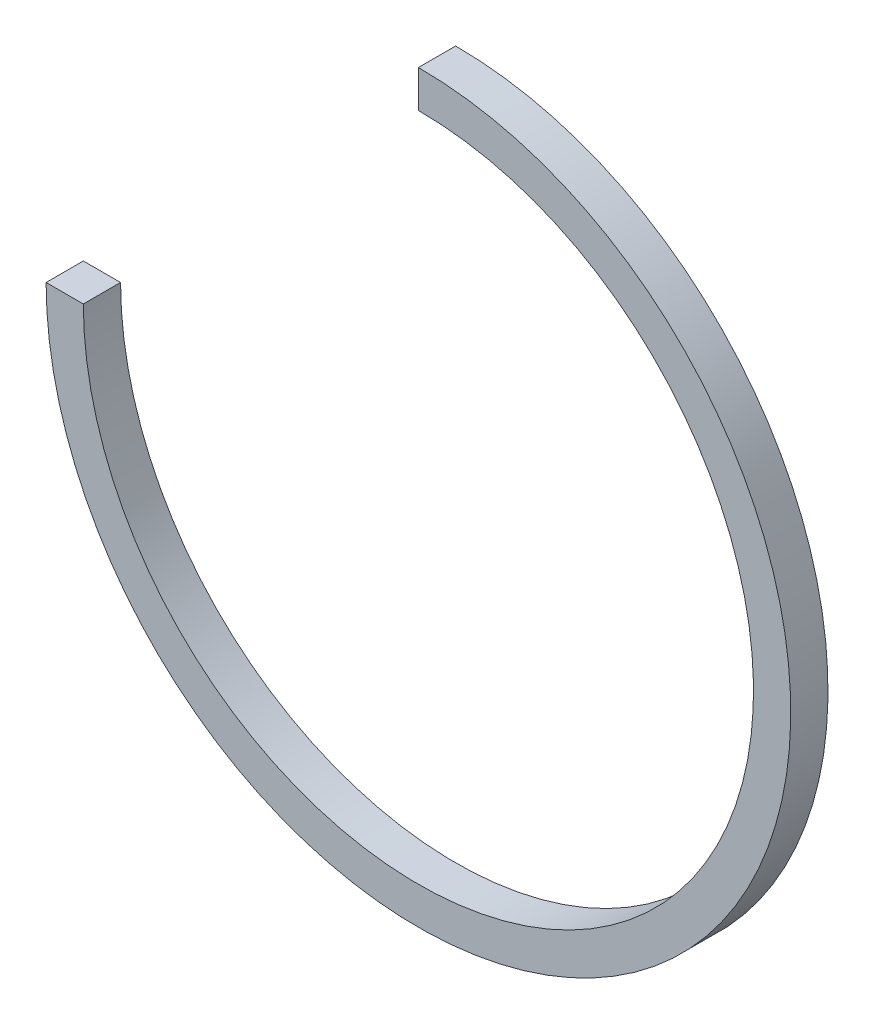
SolidWorks part; units mm, degrees
ref_plane "前视基准面" through (0, 0, 0) normal (0, 0, 1) x (1, 0, 0)
ref_plane "上视基准面" through (0, 0, 0) normal (0, 1, 0) x (1, 0, 0)
ref_plane "右视基准面" through (0, 0, 0) normal (1, 0, 0) x (0, 0, -1)
sketch "草图1" plane through (0, 0, 0) normal (0, 0, 1) x (1, 0, 0)
  line L0 (-100, 0) -> (-90, 0)
  line L1 (0, 100) -> (0, 90)
  arc A0 (0, 100) -> (-100, 0) centre (0, 0) cw
  arc A1 (-90, 0) -> (0, 90) centre (0, 0) ccw
  dimension "D2" = 90
  dimension "D1" = 100
extrude "凸台-拉伸1" add sketch "草图1" along normal blind 10
